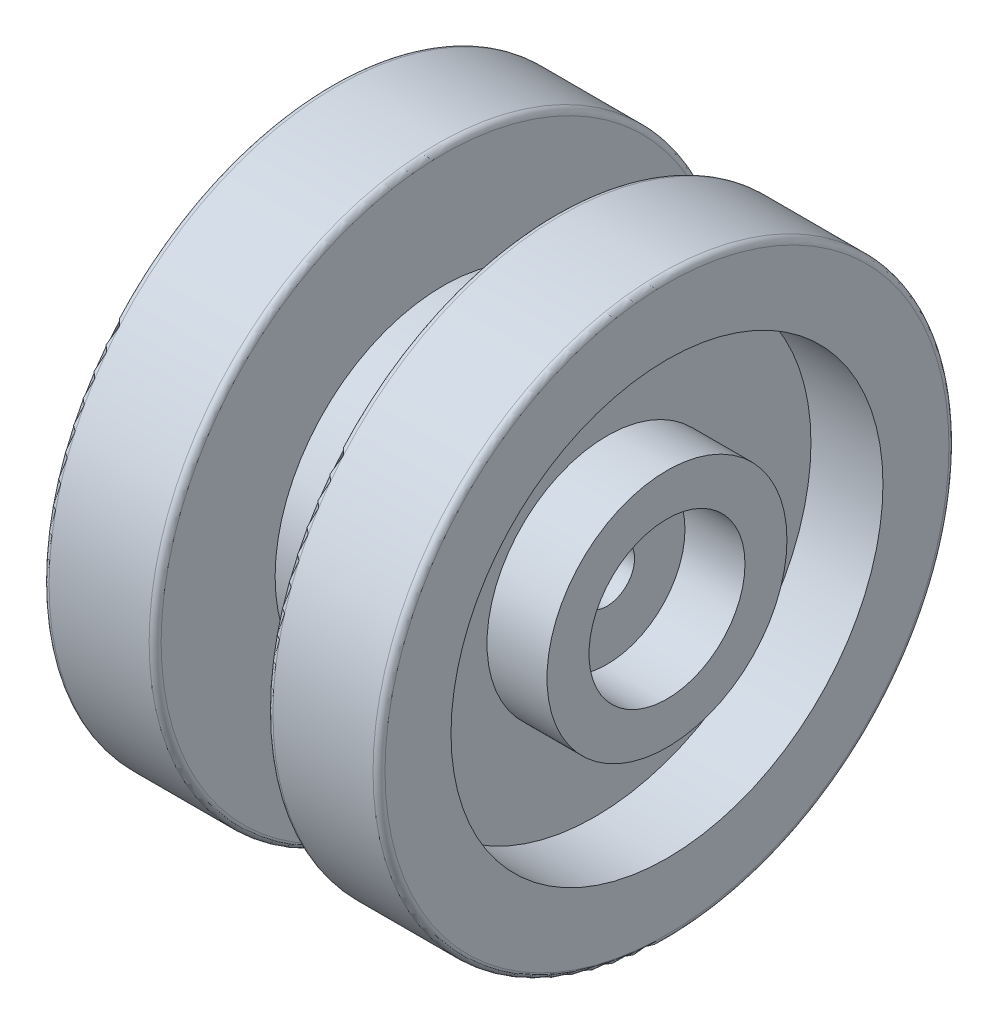
SolidWorks part; units mm, degrees
ref_plane "Front Plane" through (0, 0, 0) normal (0, 0, 1) x (1, 0, 0)
ref_plane "Top Plane" through (0, 0, 0) normal (0, 1, 0) x (1, 0, 0)
ref_plane "Right Plane" through (0, 0, 0) normal (1, 0, 0) x (0, 0, -1)
sketch "Sketch2" plane through (0, 0, 0) normal (0, 0, 1) x (1, 0, 0)
  line L0 (-2.0852, -4.4843) -> (7.2348, -4.4843)
  line L1 (-2.0852, -4.4843) -> (-2.0852, 5.5157)
  line L2 (7.2348, -4.4843) -> (7.2348, 5.5157)
  line L3 (7.2348, 5.5157) -> (16.5748, 5.5157)
  line L4 (-2.0852, 5.5157) -> (-11.4252, 5.5157)
  line L5 (-11.4252, 5.5157) -> (-11.4252, -18.4843)
  line L6 (-11.4252, -18.4843) -> (16.5748, -18.4843)
  line L7 (16.5748, -18.4843) -> (16.5748, 5.5157)
  line L8 (-11.4252, -18.4843) -> (27.3603, -18.4843) construction
  dimension "D1" = 28
  dimension "D2" = 24
  dimension "D4" = 10
  dimension "D5" = 9.32
revolve "Revolve1" add sketch "Sketch2" angle 360 about L8
sketch "Sketch3" plane through (16.5748, 0, 0) normal (1, 0, 0) x (0, 0, -1)
  circle A0 centre (0, -18.4843) radius 2
extrude "Cut-Extrude1" cut sketch "Sketch3" against normal through all
fillet "Fillet2" radius 0.5 4 edges at (-2.0852, -18.4843, 24) (7.2348, -18.4843, 24) (16.5748, -18.4843, 24) (-11.4252, -18.4843, 24)
sketch "Sketch4" plane through (16.5748, 0, 0) normal (1, 0, 0) x (0, 0, -1)
  circle A0 centre (0, -18.4843) radius 6
  circle A1 centre (0, -18.4843) radius 18
extrude "Cut-Extrude2" cut sketch "Sketch4" against normal blind 6
sketch "Sketch5" plane through (-11.4252, 0, 0) normal (-1, 0, 0) x (0, 0, 1)
  circle A0 centre (0, -18.4843) radius 6
  circle A1 centre (0, -18.4843) radius 18
extrude "Cut-Extrude3" cut sketch "Sketch5" against normal blind 6 contours A1
sketch "Sketch6" plane through (-5.4252, 0, 0) normal (-1, 0, 0) x (0, 0, 1)
  circle A0 centre (0, -18.4843) radius 10
extrude "Boss-Extrude1" add sketch "Sketch6" along normal through all
sketch "Sketch7" plane through (-11.4252, 0, 0) normal (-1, 0, 0) x (0, 0, 1)
  circle A0 centre (0, -18.4843) radius 2.3
  dimension "D1" = 4.6
sketch "Sketch8" plane through (16.5748, 0, 0) normal (1, 0, 0) x (0, 0, -1)
  circle A0 centre (0, -18.4843) radius 8
extrude "Boss-Extrude2" add sketch "Sketch8" against normal blind 10 contours A0
sketch "Sketch9" plane through (16.5748, 0, 0) normal (1, 0, 0) x (0, 0, -1)
  circle A0 centre (0, -18.4843) radius 6.5
sketch "Sketch10" plane through (-11.4252, 0, 0) normal (-1, 0, 0) x (0, 0, 1)
  circle A0 centre (0, -18.4843) radius 6.5
extrude "Cut-Extrude5" cut sketch "Sketch10" against normal blind 5 contours A0
sketch "Sketch11" plane through (16.5748, 0, 0) normal (1, 0, 0) x (0, 0, -1)
  circle A0 centre (0, -18.4843) radius 10
extrude "Boss-Extrude3" add sketch "Sketch11" against normal blind 5
sketch "Sketch12" plane through (16.5748, 0, 0) normal (1, 0, 0) x (0, 0, -1)
  circle A0 centre (0, -18.4843) radius 6.5
extrude "Cut-Extrude6" cut sketch "Sketch12" against normal blind 5
extrude "Cut-Extrude8" cut sketch "Sketch7" against normal through all contours A0
ref_plane "Plane1" through (0, 0, -14) normal (0, 0, -1) x (-1, 0, 0)
sketch "Sketch13" plane through (0, 0, -14) normal (0, 0, -1) x (-1, 0, 0)
  line L0 (2.0852, -4.4843) -> (2.0852, -32.4843) construction
  line L1 (-7.2348, -32.4843) -> (-7.2348, -4.4843) construction
  line L2 (2.0852, -4.4843) -> (2.0852, -32.4843)
  line L3 (-7.2348, -32.4843) -> (-7.2348, -4.4843)
  line L4 (-2.5748, 1.3557) -> (-2.5748, -38.3243) construction
  dimension "D1" = 4.66
